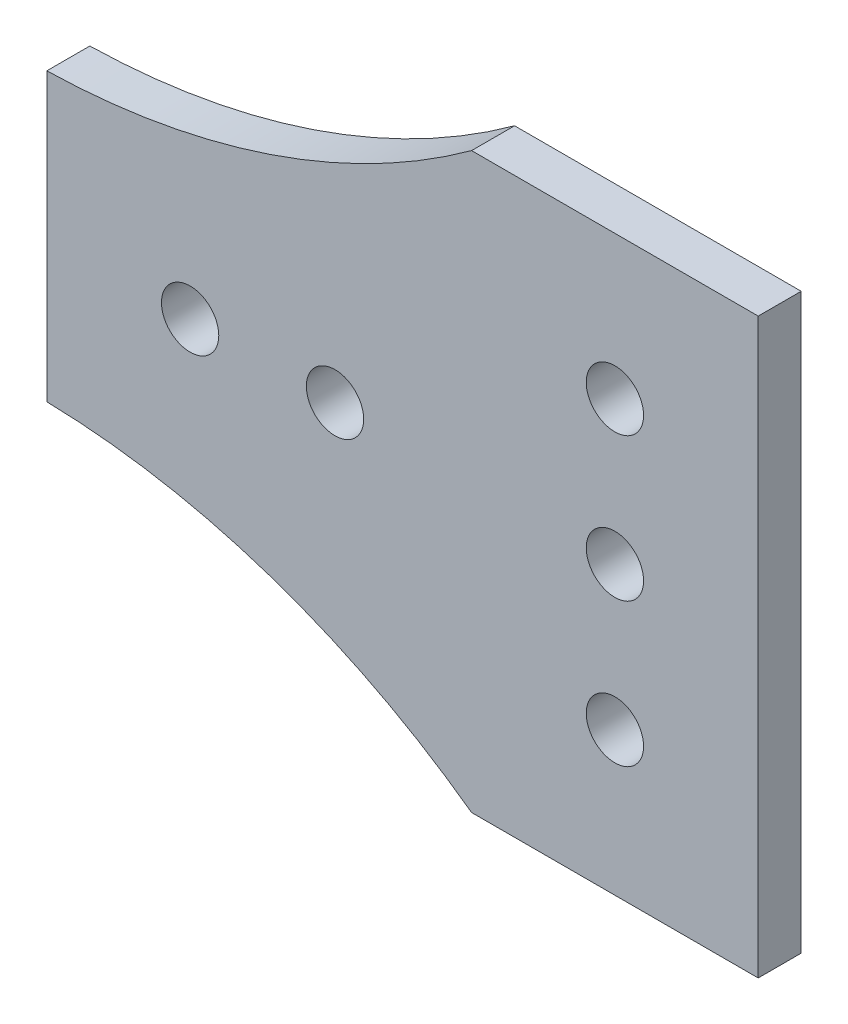
SolidWorks part; units mm, degrees
ref_plane "前视基准面" through (0, 0, 0) normal (0, 0, 1) x (1, 0, 0)
ref_plane "上视基准面" through (0, 0, 0) normal (0, 1, 0) x (1, 0, 0)
ref_plane "右视基准面" through (0, 0, 0) normal (1, 0, 0) x (0, 0, -1)
sketch "草图1" plane through (0, 0, 0) normal (0, 0, 1) x (1, 0, 0)
  line L0 (-27.3421, -0.0054) -> (-27.3421, -20.0054)
  line L1 (2.2989, -30.0054) -> (22.2989, -30.0054)
  line L2 (22.2989, -30.0054) -> (22.2989, 9.9946)
  line L3 (22.2989, 9.9946) -> (2.2989, 9.9946)
  circle A0 centre (-17.3421, -10.0054) radius 2
  circle A1 centre (-7.2316, -10.0054) radius 2
  arc A2 (-27.3421, -0.0054) -> (2.2989, 9.9946) centre (-28.5193, 52.4133) ccw
  arc A3 (2.2989, -30.0054) -> (-27.3421, -20.0054) centre (-28.5193, -72.424) ccw
  circle A4 centre (12.2989, -10.0054) radius 2
  circle A5 centre (12.2989, -0.0054) radius 2
  circle A6 centre (12.2989, -20.0054) radius 2
  dimension "D1" = 4
extrude "凸台-拉伸1" add sketch "草图1" along normal blind 3
